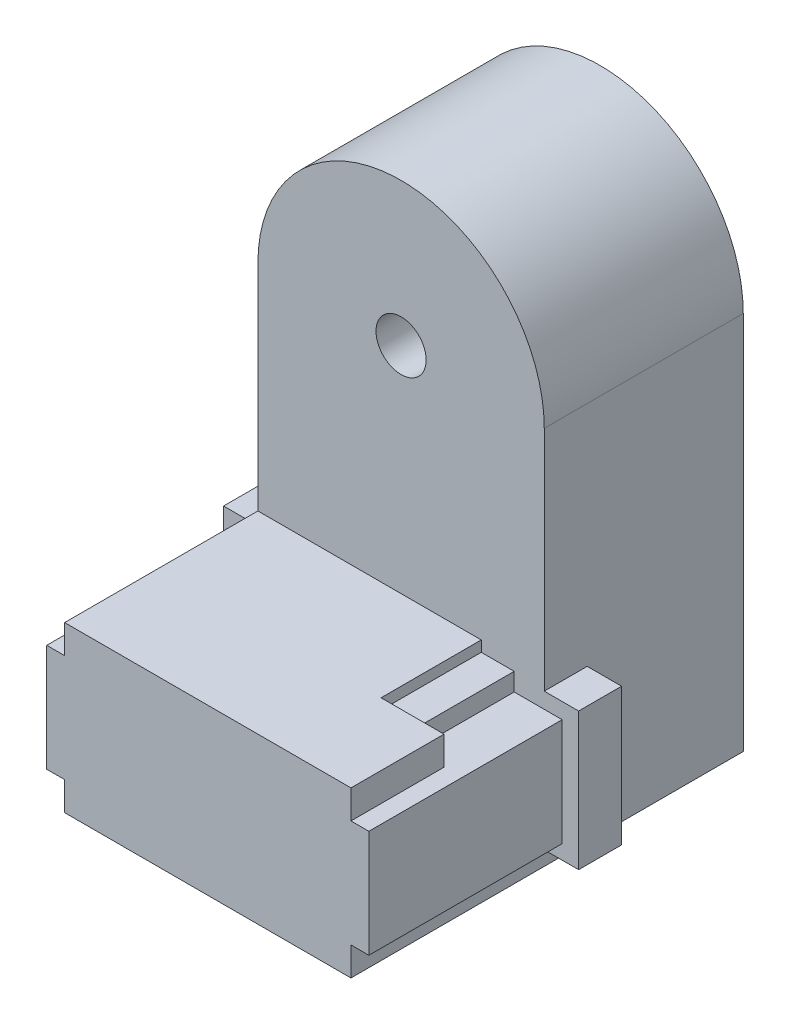
SolidWorks part; units mm, degrees
ref_plane "Front Plane" through (0, 0, 0) normal (0, 0, 1) x (1, 0, 0)
ref_plane "Top Plane" through (0, 0, 0) normal (0, 1, 0) x (1, 0, 0)
ref_plane "Right Plane" through (0, 0, 0) normal (1, 0, 0) x (0, 0, -1)
sketch "Sketch1" plane through (0, 0, 0) normal (0, 0, 1) x (1, 0, 0)
  line L1 (0, 0) -> (20, 0)
  line L2 (0, 0) -> (0, 26.5)
  line L4 (20, 0) -> (20, 26.5)
  arc A0 (20, 26.5) -> (0, 26.5) centre (10, 26.5) ccw
  dimension "D1" = 26.5
  dimension "D2" = 20
extrude "Boss-Extrude1" add sketch "Sketch1" along normal blind 13.9 contours A0 L2 L1 L4
sketch "Sketch2" plane through (0, 0, 13.9) normal (0, 0, 1) x (1, 0, 0)
  line L0 (0, 0) -> (20, 0) construction
  line L1 (0, 0) -> (20, 0)
  line L2 (0, 0) -> (0, 11.5)
  line L3 (0, 11.5) -> (20, 11.5)
  line L4 (20, 0) -> (20, 11.5)
  line L5 (0, 0) -> (0, 26.5) construction
  point P4 (10, 0)
  point P7 (10, 0)
  dimension "D2" = 11.5
extrude "Boss-Extrude2" add sketch "Sketch2" along normal blind 13.5
sketch "Sketch4" plane through (0, 0, 13.9) normal (0, 0, 1) x (1, 0, 0)
  line L0 (0, 0) -> (20, 0) construction
  line L1 (-2.4, 10.6) -> (22.4, 10.6)
  line L2 (-2.4, 10.6) -> (-2.4, 1)
  line L3 (-2.4, 1) -> (22.4, 1)
  line L4 (22.4, 10.6) -> (22.4, 1)
  line L5 (10, 0) -> (10, 11.5) construction
  line L6 (20, 11.5) -> (0, 11.5) construction
  point P10 (10, 1)
  dimension "D1" = 9.6
  dimension "D2" = 10.6
  dimension "D3" = 24.8
extrude "Boss-Extrude3" add sketch "Sketch4" against normal blind 3
sketch "Sketch5" plane through (0, 0, 27.4) normal (0, 0, 1) x (1, 0, 0)
  line L0 (10, 11.5) -> (10, 0) construction
  line L1 (-1.25, 2) -> (21.25, 2)
  line L2 (-1.25, 2) -> (-1.25, 9.5)
  line L3 (-1.25, 9.5) -> (21.25, 9.5)
  line L4 (21.25, 2) -> (21.25, 9.5)
  line L5 (20, 11.5) -> (0, 11.5) construction
  line L6 (0, 0) -> (20, 0) construction
  point P10 (10, 2)
  dimension "D1" = 7.5
  dimension "D2" = 22.5
  dimension "D3" = 2
extrude "Boss-Extrude4" add sketch "Sketch5" against normal up to next
sketch "Sketch6" plane through (0, 0, 13.9) normal (0, 0, 1) x (1, 0, 0)
  line L0 (20, 9.5) -> (21.25, 9.5) construction
  line L1 (20, 11.5) -> (15.6, 11.5)
  line L2 (20, 11.5) -> (20, 9.5)
  line L3 (20, 9.5) -> (17.9, 9.5)
  line L4 (15.6, 11.5) -> (15.6, 10.75)
  line L5 (10, 11.5) -> (10, 0) construction
  line L6 (20, 11.5) -> (0, 11.5) construction
  line L7 (0, 0) -> (20, 0) construction
  line L8 (0, 0) -> (0, 2)
  line L9 (0, 0) -> (4.4, 0)
  line L10 (4.4, 0) -> (4.4, 0.75)
  line L11 (0, 2) -> (2.1, 2)
  line L12 (22.4, 1) -> (22.4, 10.6) construction
  line L15 (15.6, 10.75) -> (17.9, 10.75)
  line L16 (17.9, 9.5) -> (17.9, 10.75)
  line L19 (2.1, 2) -> (2.1, 0.75)
  line L20 (4.4, 0.75) -> (2.1, 0.75)
  point P13 (10, 5.75)
  point P20 (10, 5.75)
  point P24 (17.9, 10.125)
  point P31 (10, 5.75)
  dimension "D3" = 4.5
  dimension "D4" = 0.75
  dimension "D2" = 2
  dimension "D5" = 2
extrude "Cut-Extrude1" cut sketch "Sketch6" along normal blind 7
sketch "Sketch7" plane through (0, 0, 0) normal (0, 0, -1) x (-1, 0, 0)
  line L0 (-20, 26.5) -> (0, 26.5) construction
  circle A0 centre (-10, 26.5) radius 1.75
  dimension "D1" = 3.5
extrude "Cut-Extrude2" cut sketch "Sketch7" against normal up to surface (13.9 mm away) contours A0 up to face at (16.7357, 10.9786, 13.9)
